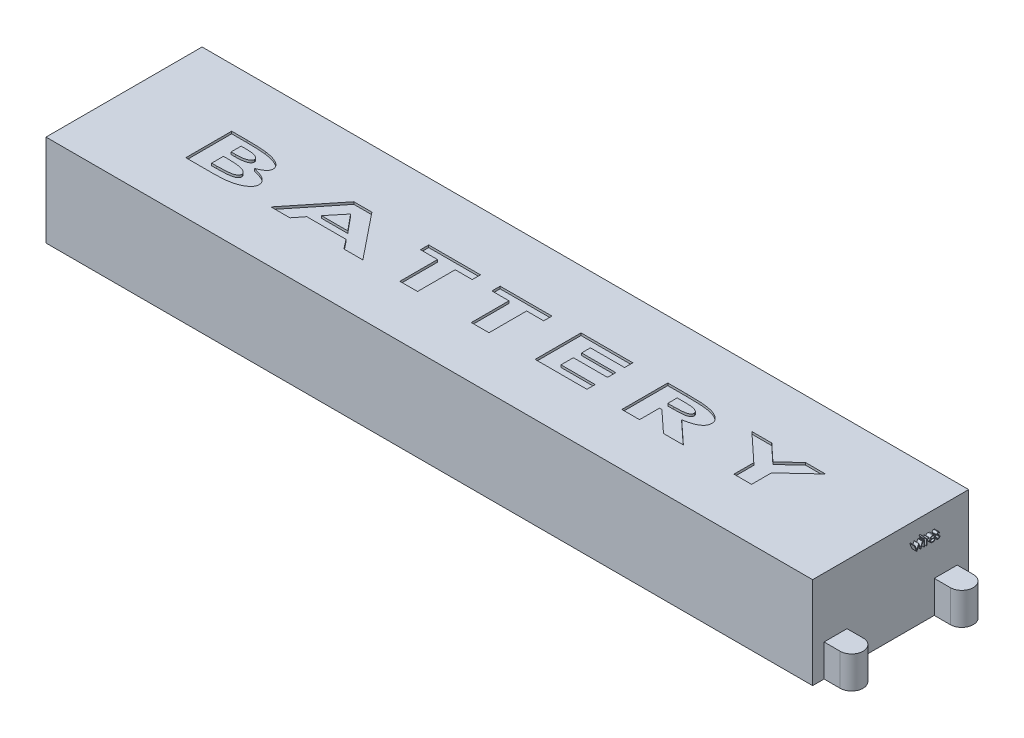
SolidWorks part; units mm, degrees
ref_plane "Front Plane" through (0, 0, 0) normal (0, 0, 1) x (1, 0, 0)
ref_plane "Top Plane" through (0, 0, 0) normal (0, 1, 0) x (1, 0, 0)
ref_plane "Right Plane" through (0, 0, 0) normal (1, 0, 0) x (0, 0, -1)
sketch "Sketch1" plane through (0, 0, 0) normal (0, 1, 0) x (1, 0, 0)
  line L1 (-167, 34) -> (167, 34)
  line L2 (-167, 34) -> (-167, -34)
  line L3 (-167, -34) -> (167, -34)
  line L4 (167, 34) -> (167, -34)
  line L5 (-167, 34) -> (167, -34) construction
  line L6 (-167, -34) -> (167, 34) construction
  point P0 (0, 0)
  dimension "D1" = 334
  dimension "D2" = 68
extrude "Boss-Extrude1" add sketch "Sketch1" along normal blind 40
sketch "Sketch4" plane through (0, 0, 0) normal (0, 1, 0) x (1, 0, 0)
  line L0 (167, -19) -> (174, -19)
  line L1 (167, -34) -> (167, 34) construction
  line L2 (167, -29) -> (174, -29)
  line L3 (-167, -34) -> (167, -34) construction
  line L4 (167, -29) -> (167, -19)
  arc A0 (174, -19) -> (174, -29) centre (174, -24) cw
  dimension "D1" = 5
  dimension "D2" = 7
  dimension "D3" = 5
extrude "Boss-Extrude3" add sketch "Sketch4" along normal blind 14
mirror "Mirror1" about plane through (0, 0, 0) normal (0, 0, 1) of "Boss-Extrude3"
sketch "Sketch2" plane through (167, 0, 0) normal (1, 0, 0) x (0, 0, -1)
  line L0 (4, 30) -> (24, 30) construction
  line L1 (34, 40) -> (34, 0) construction
  line L2 (-34, 40) -> (34, 40) construction
  text T0 "wires"
  point P4 (32.429, 31.1836)
  dimension "D1" = 20
  dimension "D2" = 10
  dimension "D3" = 10
extrude "Boss-Extrude2" add sketch "Sketch2" along normal blind 2
sketch "Sketch3" plane through (0, 40, 0) normal (0, 1, 0) x (1, 0, 0)
  line L0 (-167, -11.3333) -> (167, -11.3333) construction
  line L1 (-167, 34) -> (-167, -34) construction
  line L2 (167, -34) -> (167, 34) construction
  line L3 (-167, -34) -> (167, -34) construction
  text T0 "<b>BATTERY</b>" font "Century Gothic" height 20
  dimension "D1" = 22.6667
extrude "Cut-Extrude1" cut sketch "Sketch3" against normal blind 1
